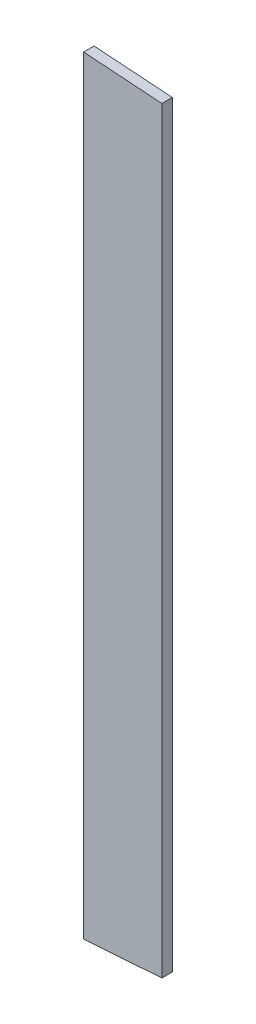
SolidWorks part; units mm, degrees
ref_plane "Front Plane" through (0, 0, 0) normal (0, 0, 1) x (1, 0, 0)
ref_plane "Top Plane" through (0, 0, 0) normal (0, 1, 0) x (1, 0, 0)
ref_plane "Right Plane" through (0, 0, 0) normal (1, 0, 0) x (0, 0, -1)
sketch "Sketch1" plane through (0, 0, 2758.55) normal (0, 0, 1) x (1, 0, 0)
  line L0 (-49.7697, 346.1083) -> (-64.7697, 345.0594)
  line L1 (-140.9262, 339.734) -> (58.5866, 353.6853) construction
  line L2 (-64.7697, 345.0594) -> (-64.7697, 492.4158)
  line L3 (58.5866, 483.7899) -> (-140.9262, 497.7412) construction
  line L4 (-64.7697, 492.4158) -> (-49.7697, 491.3669)
  line L5 (-49.7697, 491.3669) -> (-49.7697, 346.1083)
  dimension "D1" = 15
extrude "Boss-Extrude1" add sketch "Sketch1" along normal blind 2
ref_plane "Plane1" through (-57.2697, 0, 0) normal (1, 0, 0) x (0, 0, -1)
